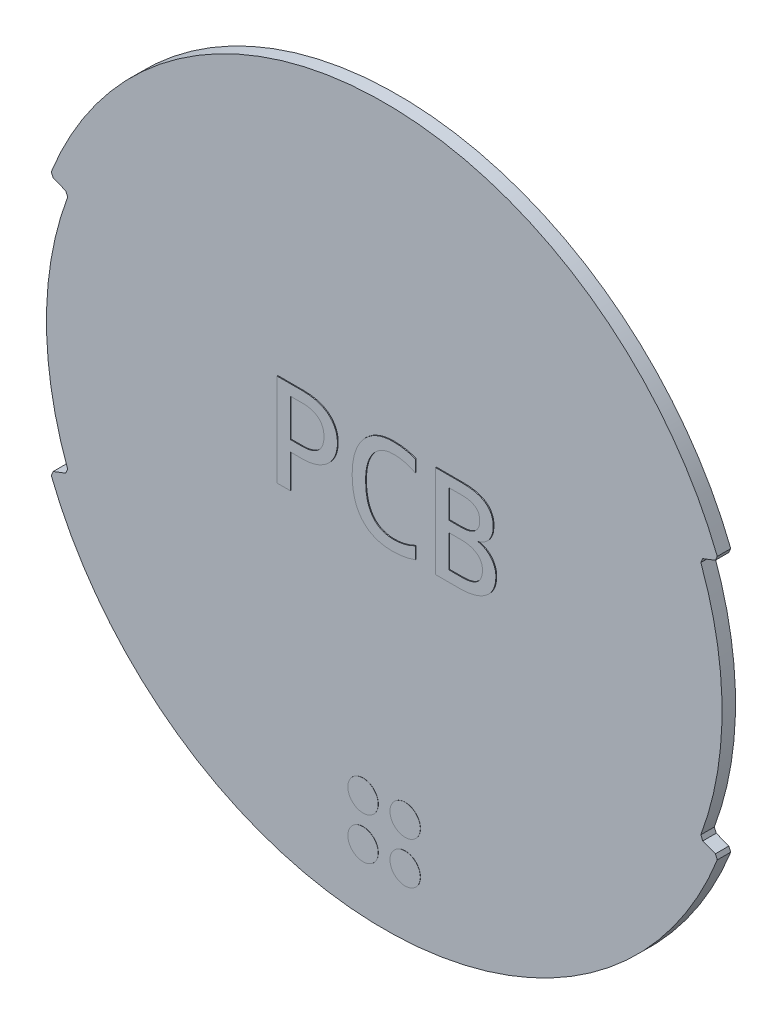
SolidWorks part; units mm, degrees
material "A-玻璃纤维"
ref_plane "前视基准面" through (0, 0, 0) normal (0, 0, 1) x (1, 0, 0)
ref_plane "上视基准面" through (0, 0, 0) normal (0, 1, 0) x (1, 0, 0)
ref_plane "右视基准面" through (0, 0, 0) normal (1, 0, 0) x (0, 0, -1)
sketch "草图1" plane through (0, 0, 0) normal (0, 0, 1) x (1, 0, 0)
  line L0 (13.4157, -14.1516) -> (19.3517, -2.4004) construction
  line L1 (-13.4157, 14.1516) -> (-19.3517, 2.4004) construction
  line L2 (13.4157, -14.1516) -> (19.3517, -2.4004) construction
  line L3 (-13.4157, 14.1516) -> (-19.3517, 2.4004) construction
  line L4 (2.55, -18.945) -> (-2.55, -18.945) construction
  line L5 (2.7, -13.695) -> (2.7, -18.795) construction
  line L6 (-2.55, -13.545) -> (2.55, -13.545) construction
  line L7 (-2.7, -18.795) -> (-2.7, -13.695) construction
  line L8 (2.55, -18.945) -> (-2.55, -18.945) construction
  line L9 (2.7, -13.695) -> (2.7, -18.795) construction
  line L10 (-2.55, -13.545) -> (2.55, -13.545) construction
  line L11 (-2.7, -18.795) -> (-2.7, -13.695) construction
  arc A0 (7.3321, -19.945) -> (-7.3321, -19.945) centre (0, 0) ccw
  arc A1 (7.3321, -19.945) -> (-7.3321, -19.945) centre (0, 0) cw
  arc A13 (19.3517, -2.4004) -> (-13.4157, 14.1516) centre (0, 0) ccw construction
  arc A14 (-19.3517, 2.4004) -> (13.4157, -14.1516) centre (0, 0) ccw construction
  arc A15 (19.3517, -2.4004) -> (-13.4157, 14.1516) centre (0, 0) ccw construction
  arc A16 (-19.3517, 2.4004) -> (13.4157, -14.1516) centre (0, 0) ccw construction
  arc A17 (-2.7, -18.795) -> (-2.55, -18.945) centre (-2.55, -18.795) ccw construction
  arc A18 (2.55, -18.945) -> (2.7, -18.795) centre (2.55, -18.795) ccw construction
  arc A19 (2.7, -13.695) -> (2.55, -13.545) centre (2.55, -13.695) ccw construction
  arc A20 (-2.55, -13.545) -> (-2.7, -13.695) centre (-2.55, -13.695) ccw construction
  arc A21 (-2.7, -18.795) -> (-2.55, -18.945) centre (-2.55, -18.795) ccw construction
  arc A22 (2.55, -18.945) -> (2.7, -18.795) centre (2.55, -18.795) ccw construction
  arc A23 (2.7, -13.695) -> (2.55, -13.545) centre (2.55, -13.695) ccw construction
  arc A24 (-2.55, -13.545) -> (-2.7, -13.695) centre (-2.55, -13.695) ccw construction
  point P3 (0, -19.945)
  dimension "D1" = 42.5
extrude "凸台-拉伸1" add sketch "草图1" along normal blind 0.8
sketch "草图3" plane through (0, 0, 0) normal (0, 0, -1) x (-1, 0, 0)
  line L0 (0, -16.245) -> (0, 0.0046) construction
  line L3 (-2.7, -13.545) -> (2.7, -13.545) construction
  line L4 (-2.7, -13.545) -> (-2.7, -18.945) construction
  line L5 (-2.7, -18.945) -> (2.7, -18.945) construction
  line L6 (2.7, -13.545) -> (2.7, -18.945) construction
  line L7 (-2.7, -13.545) -> (2.7, -18.945) construction
  line L8 (-2.7, -18.945) -> (2.7, -13.545) construction
  line L9 (-2.7, -16.245) -> (2.7, -16.245) construction
  circle A0 centre (-1.25, -14.995) radius 0.9
  circle A3 centre (1.25, -14.995) radius 0.9
  circle A4 centre (1.25, -17.495) radius 0.9
  circle A5 centre (-1.25, -17.495) radius 0.9
  point P0 (0, -16.245)
  dimension "D6" = 1.8
  dimension "D2" = 5.4
  dimension "D3" = 5.4
  dimension "D5" = 2.5
sketch "草图4" plane through (0, 0, 0.8) normal (0, 0, 1) x (1, 0, 0)
  text T0 "PCB" font "Consolas" height 5.5
  point P1 (-6.3763, -0.2119)
  point P2 (-6.78, -1.6906)
  point P3 (-5.981, -2.1536)
  point P4 (0, 0)
  point P5 (-6.7658, -1.9177)
  point P6 (0, 0)
  point P7 (0, 0)
  point P8 (0, 0)
  point P9 (-7.161, -1.3797)
  point P10 (0, 0)
  point P11 (0, 0)
  point P12 (0, 0)
  point P13 (0, 0)
  point P14 (-6.9562, -1.4444)
extrude "凸台-拉伸2" add sketch "草图4" along normal blind 0.05 and the other way blind 0.85 separate body
extrude "凸台-拉伸3" add sketch "草图3" along normal blind 0.01 and the other way blind 0.81 separate body
sketch "草图5" plane through (0, 0, 0.8) normal (0, 0, 1) x (1, 0, 0)
  line L0 (0, 0) -> (50000, 0) construction
  line L1 (0, 0) -> (19.8386, 7.6153) construction
  line L2 (19.8386, 7.6153) -> (18.7183, 7.1853)
  line L3 (0, 0) -> (19.8386, -7.6153) construction
  line L4 (19.8386, -7.6153) -> (18.7183, -7.1853)
  line L5 (0, 0.9042) -> (0, -49999.0958) construction
  line L6 (-19.8386, -7.6153) -> (-18.7183, -7.1853)
  line L7 (-19.8386, 7.6153) -> (-18.7183, 7.1853)
  arc A0 (19.8386, 7.6153) -> (19.8386, -7.6153) centre (0, 0) cw
  circle A1 centre (0, 0) radius 21.25 construction
  arc A2 (18.7183, 7.1853) -> (18.7183, -7.1853) centre (0, 0) cw
  arc A3 (-18.7183, 7.1853) -> (-18.7183, -7.1853) centre (0, 0) ccw
  arc A4 (-19.8386, 7.6153) -> (-19.8386, -7.6153) centre (0, 0) ccw
  dimension "D1" = 21
  dimension "D2" = 1.2
extrude "切除-拉伸3" cut sketch "草图5" against normal through all
chamfer "倒角2" distance 0.2 angle 45 8 edges at (18.7183, -7.1853, 0.4) (19.8386, -7.6153, 0.4) (19.8386, 7.6153, 0.4) (18.7183, 7.1853, 0.4) (-19.8386, 7.6153, 0.4) (-18.7183, 7.1853, 0.4) (-19.8386, -7.6153, 0.4) (-18.7183, -7.1853, 0.4)
